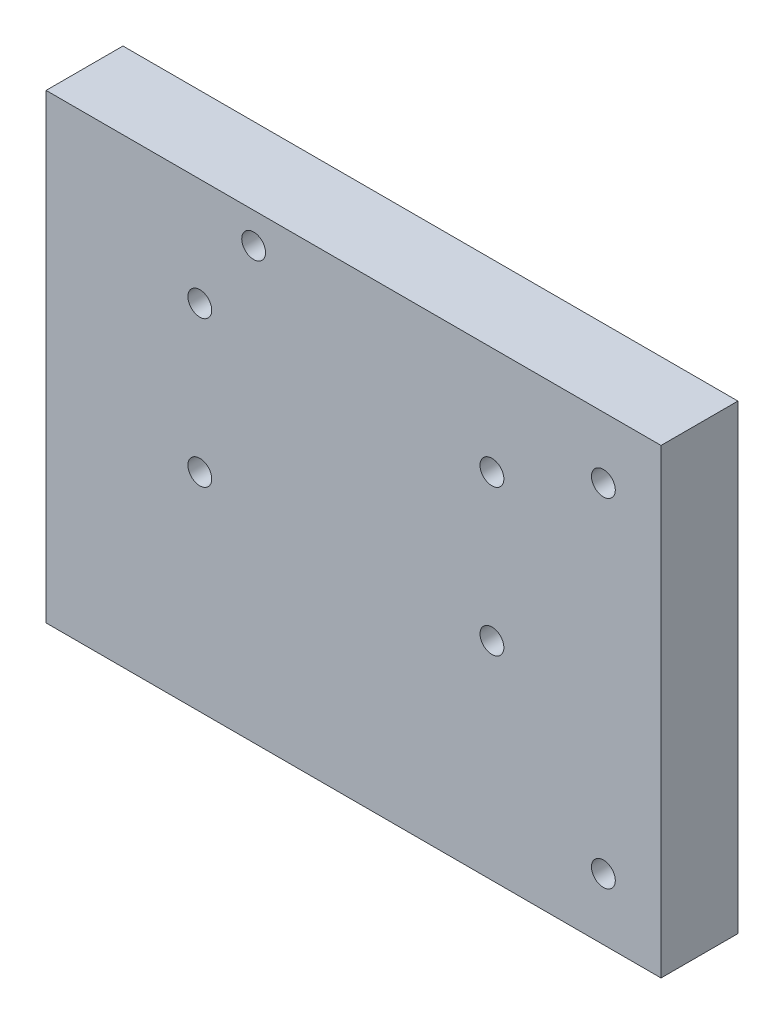
SolidWorks part; units mm, degrees
ref_plane "Front" through (0, 0, 0) normal (0, 0, 1) x (1, 0, 0)
ref_plane "Top" through (0, 0, 0) normal (0, 1, 0) x (1, 0, 0)
ref_plane "Right" through (0, 0, 0) normal (1, 0, 0) x (0, 0, -1)
sketch "Sketch1" plane through (0, 0, 0) normal (0, 0, 1) x (1, 0, 0)
  line L1 (-40, -30) -> (40, -30)
  line L2 (-40, -30) -> (-40, 30)
  line L3 (-40, 30) -> (40, 30)
  line L4 (40, -30) -> (40, 30)
  line L5 (-40, -30) -> (40, 30) construction
  line L6 (-40, 30) -> (40, -30) construction
  line L7 (-20, 16) -> (18, 16) construction
  line L8 (-20, 16) -> (-20, -3) construction
  line L9 (-20, -3) -> (18, -3) construction
  line L10 (18, 16) -> (18, -3) construction
  line L11 (-20, 16) -> (18, -3) construction
  line L12 (-20, -3) -> (18, 16) construction
  circle A0 centre (-20, 16) radius 1.55
  circle A1 centre (18, 16) radius 1.55
  circle A2 centre (18, -3) radius 1.55
  circle A3 centre (-20, -3) radius 1.55
  point P0 (0, 0)
  point P5 (-1, 6.5)
  dimension "D5" = 3.1
  dimension "D6" = 3.1
  dimension "D7" = 3.1
  dimension "D8" = 3.1
  dimension "D9" = 14
  dimension "D10" = 20
  dimension "D1" = 60
  dimension "D2" = 80
  dimension "D3" = 19
  dimension "D4" = 38
extrude "Boss-Extrude1" add sketch "Sketch1" along normal blind 10
sketch "Sketch2" plane through (0, 0, 0) normal (0, 0, -1) x (-1, 0, 0)
  line L0 (40, 30) -> (40, -30) construction
  line L1 (-40, 30) -> (40, 30) construction
  circle A0 centre (13, 26) radius 1.55
  dimension "D1" = 3.1
  dimension "D2" = 27
  dimension "D3" = 4
extrude "Cut-Extrude1" cut sketch "Sketch2" against normal up to next
sketch "Sketch3" plane through (0, 0, 10) normal (0, 0, 1) x (1, 0, 0)
  line L0 (40, 30) -> (-40, 30) construction
  line L1 (-40, -30) -> (40, -30) construction
  line L2 (40, -30) -> (40, 30) construction
  circle A0 centre (32.5, 22) radius 1.55
  circle A1 centre (32.5, -22) radius 1.55
  dimension "D1" = 3.1
  dimension "D2" = 3.1
  dimension "D5" = 7.5
  dimension "D3" = 8
  dimension "D4" = 8
extrude "Cut-Extrude2" cut sketch "Sketch3" against normal up to next
